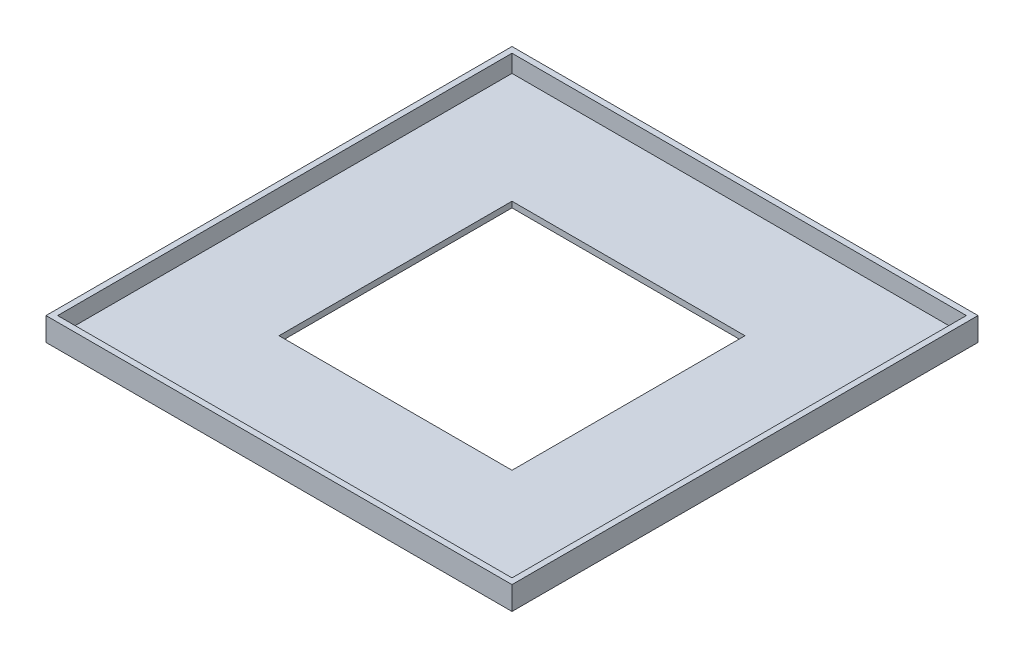
SolidWorks part; units mm, degrees
ref_plane "Front Plane" through (0, 0, 0) normal (0, 0, 1) x (1, 0, 0)
ref_plane "Top Plane" through (0, 0, 0) normal (0, 1, 0) x (1, 0, 0)
ref_plane "Right Plane" through (0, 0, 0) normal (1, 0, 0) x (0, 0, -1)
sketch "Sketch1" plane through (0, 0, 0) normal (0, 1, 0) x (1, 0, 0)
  line L1 (-100, 100) -> (100, 100)
  line L2 (-100, 100) -> (-100, -100)
  line L3 (-100, -100) -> (100, -100)
  line L4 (100, 100) -> (100, -100)
  point P4 (100, 0)
  point P7 (0, -100)
  dimension "D1" = 200
  dimension "D2" = 200
extrude "Boss-Extrude1" add sketch "Sketch1" along normal blind 10
shell "Shell1" thickness 2.5
sketch "Sketch2" plane through (0, 2.5, 0) normal (0, 1, 0) x (1, 0, 0)
  line L1 (-50, 50) -> (50, 50)
  line L2 (-50, 50) -> (-50, -50)
  line L3 (-50, -50) -> (50, -50)
  line L4 (50, 50) -> (50, -50)
  point P4 (50, 0)
  point P6 (0, -50)
  dimension "D1" = 100
  dimension "D2" = 100
extrude "Cut-Extrude1" cut sketch "Sketch2" against normal through all
